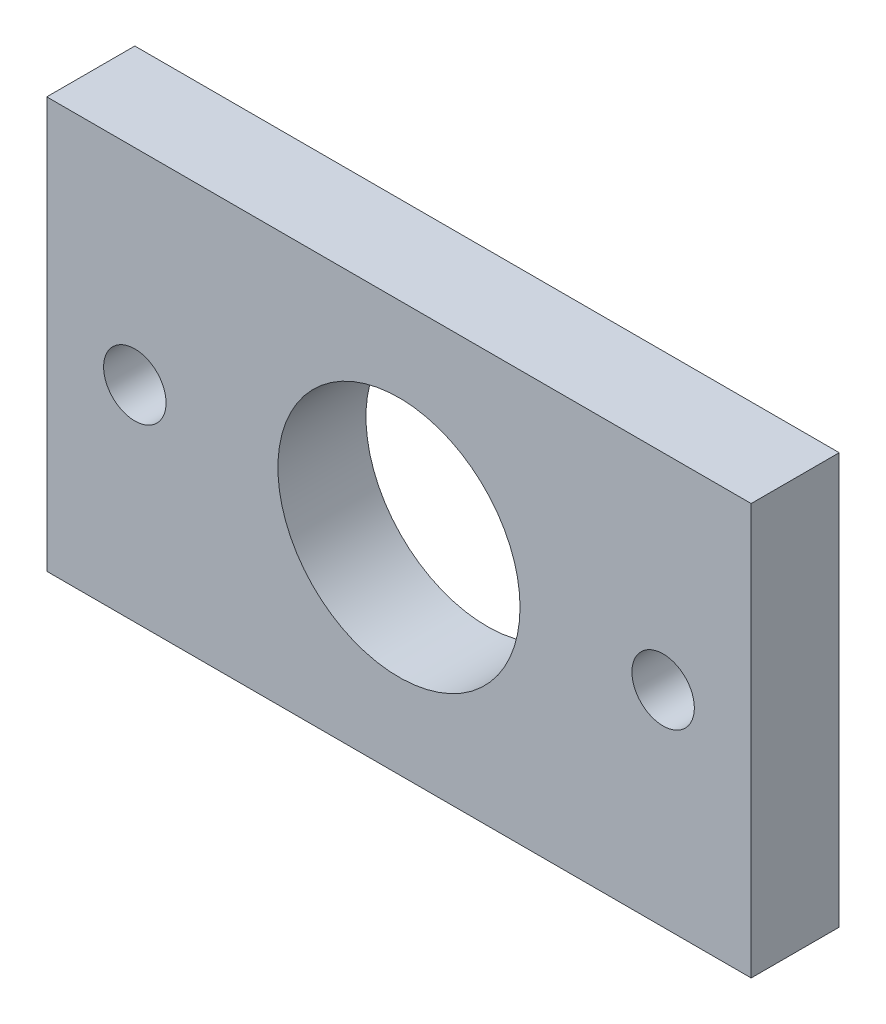
SolidWorks part; units mm, degrees
ref_plane "Front" through (0, 0, 0) normal (0, 0, 1) x (1, 0, 0)
ref_plane "Top" through (0, 0, 0) normal (0, 1, 0) x (1, 0, 0)
ref_plane "Right" through (0, 0, 0) normal (1, 0, 0) x (0, 0, -1)
sketch "Sketch1" plane through (0, 0, 0) normal (0, 0, 1) x (1, 0, 0)
  line L1 (-38.1, -22.225) -> (38.1, -22.225)
  line L2 (-38.1, -22.225) -> (-38.1, 22.225)
  line L3 (-38.1, 22.225) -> (38.1, 22.225)
  line L4 (38.1, -22.225) -> (38.1, 22.225)
  line L5 (-38.1, -22.225) -> (38.1, 22.225) construction
  line L6 (-38.1, 22.225) -> (38.1, -22.225) construction
  point P0 (0, 0)
  dimension "D1" = 44.45
  dimension "D2" = 76.2
extrude "Boss-Extrude1" add sketch "Sketch1" along normal blind 9.525
sketch "Sketch3" plane through (0, 0, 9.525) normal (0, 0, 1) x (1, 0, 0)
  line L1 (28.575, 0) -> (-28.575, 0) construction
  point P0 (0, 0)
  point P4 (0, 0)
  dimension "D2" = 57.15
hole_wizard "1 Clearance Hole1" positions "Sketch5" profile "Sketch4" hole size "1" standard "ANSI Inch" end condition through all
sketch "Sketch5" plane through (0, 0, 9.525) normal (0, 0, 1) x (1, 0, 0)
  point P0 (0, 0)
sketch "Sketch4" plane through (0, 0, 9.525) normal (1, 0, 0) x (0, -1, 0)
  line L0 (0, 0) -> (0, 9.525)
  line L1 (0, 9.525) -> (13.0962, 9.525)
  line L2 (13.0962, 9.525) -> (13.0962, 0)
  line L5 (13.0962, 0) -> (0, 0)
  line L11 (0, -6.35) -> (0, 107.95) construction
  dimension "Thru Hole Dia." = 26.1925
  dimension "Thru Hole Depth" = 9.525
hole_wizard "1/4 Clearance Hole1" positions "Sketch7" profile "Sketch6" hole size "1/4" standard "ANSI Inch" end condition through all
sketch "Sketch7" plane through (0, 0, 9.525) normal (0, 0, 1) x (1, 0, 0)
  point P0 (-28.575, 0)
  point P3 (28.575, 0)
sketch "Sketch6" plane through (-28.575, 0, 9.525) normal (1, 0, 0) x (0, -1, 0)
  line L0 (0, 0) -> (0, 9.525)
  line L1 (0, 9.525) -> (3.3782, 9.525)
  line L2 (3.3782, 9.525) -> (3.3782, 0)
  line L5 (3.3782, 0) -> (0, 0)
  line L11 (0, -6.35) -> (0, 107.95) construction
  dimension "Thru Hole Dia." = 6.7564
  dimension "Thru Hole Depth" = 9.525
